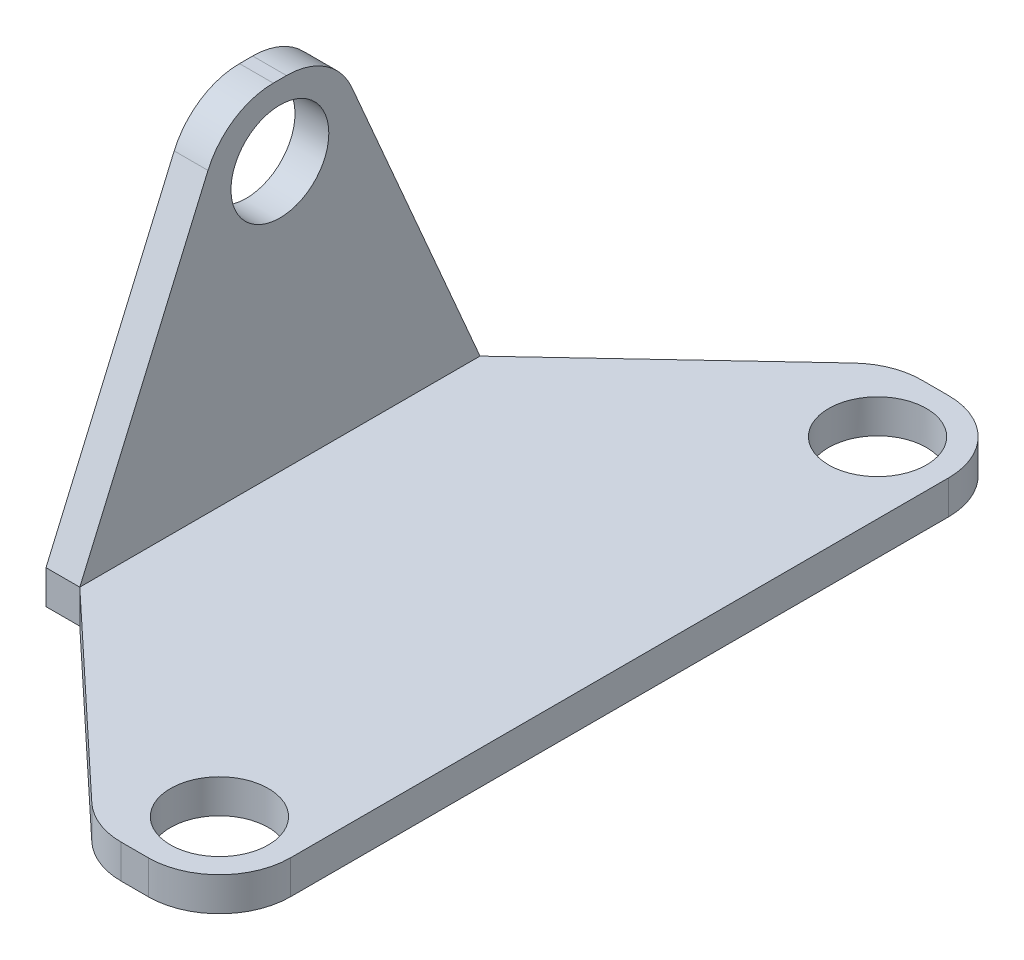
SolidWorks part; units mm, degrees
material "Ferro dúctil"
ref_plane "Plano frontal" through (0, 0, 0) normal (0, 0, 1) x (1, 0, 0)
ref_plane "Plano superior" through (0, 0, 0) normal (0, 1, 0) x (1, 0, 0)
ref_plane "Plano direito" through (0, 0, 0) normal (1, 0, 0) x (0, 0, -1)
sketch "Esboço1" plane through (0, 0, 0) normal (0, 0, 1) x (1, 0, 0)
  line L0 (-16.8226, 6.0968) -> (-16.8226, -14.9032)
  line L1 (-16.8226, -14.9032) -> (4.1774, -14.9032)
  dimension "D1" = 21
  dimension "D2" = 21
ref_plane "Plano1" through (4.1774, 0, 0) normal (1, 0, 0) x (0, 0, -1)
sketch "Esboço3" plane through (4.1774, 0, 0) normal (1, 0, 0) x (0, 0, -1)
  line L11 (22.5, -14.9032) -> (22.5, -13.0032)
  line L12 (22.5, -13.0032) -> (-22.5, -13.0032)
  line L13 (-22.5, -13.0032) -> (-22.5, -14.9032)
  line L15 (-22.5, -14.9032) -> (22.5, -14.9032)
  point P0 (0, -14.9032)
  dimension "D1" = 1.9
  dimension "D2" = 45
sweep "Varredura2" add profiles "Esboço3" path "Esboço1"
sketch "Esboço4" plane through (-14.9226, 0, 0) normal (1, 0, 0) x (0, 0, -1)
  line L0 (0, 6.0968) -> (0, -14.9032) construction
  line L1 (0, 6.0968) -> (-3, 6.0968)
  line L2 (22.5, 6.0968) -> (-22.5, 6.0968) construction
  line L3 (-3, 6.0968) -> (-11.25, -13.0032)
  line L4 (-22.5, -13.0032) -> (22.5, -13.0032) construction
  line L5 (-11.25, -13.0032) -> (-24.2498, -13.0032)
  line L6 (-24.2498, -13.0032) -> (-24.2498, 8.862)
  line L7 (-24.2498, 8.862) -> (24.2498, 8.862)
  line L8 (24.2498, 8.862) -> (24.2498, -13.0032)
  line L9 (24.2498, -13.0032) -> (11.25, -13.0032)
  line L10 (11.25, -13.0032) -> (3, 6.0968)
  line L11 (3, 6.0968) -> (0, 6.0968)
  circle A0 centre (0, 2.0968) radius 2.75
  dimension "D1" = 5.5
  dimension "D2" = 4
  dimension "D3" = 22.5
  dimension "D4" = 3
extrude "Corte-extrusão1" cut sketch "Esboço4" against normal through all both and the other way through all
sketch "Esboço5" plane through (0, -13.0032, 0) normal (0, 1, 0) x (1, 0, 0)
  line L0 (-14.9226, -11.25) -> (-18.8897, -11.25)
  line L1 (-18.8897, -11.25) -> (-18.8897, -25.4134)
  line L2 (-18.8897, -25.4134) -> (7.4547, -25.4134)
  line L3 (7.4547, -25.4134) -> (7.4547, -2.1876)
  line L4 (7.4547, -2.1876) -> (4.1774, -2.1876)
  line L5 (4.1774, 22.5) -> (4.1774, -22.5) construction
  line L6 (4.1774, -2.1876) -> (4.1774, -22.5)
  line L7 (4.1774, -22.5) -> (-2.9248, -22.5)
  line L8 (-14.9226, -22.5) -> (4.1774, -22.5) construction
  line L9 (-2.9248, -22.5) -> (-14.9226, -11.25)
  circle A0 centre (0.1774, -18.5) radius 2.75
  dimension "D1" = 5.5
  dimension "D2" = 4
  dimension "D3" = 4
extrude "Corte-extrusão2" cut sketch "Esboço5" against normal through all both and the other way through all
mirror "Espelhar1" about plane through (0, 0, 0) normal (0, 0, 1) of "Corte-extrusão2"
fillet "Filete1" radius 4 6 edges at (-2.9248, -13.9532, -22.5) (4.1774, -13.9532, -22.5) (4.1774, -13.9532, 22.5) (-2.9248, -13.9532, 22.5) (-15.8726, 6.0968, -3) (-15.8726, 6.0968, 3)
